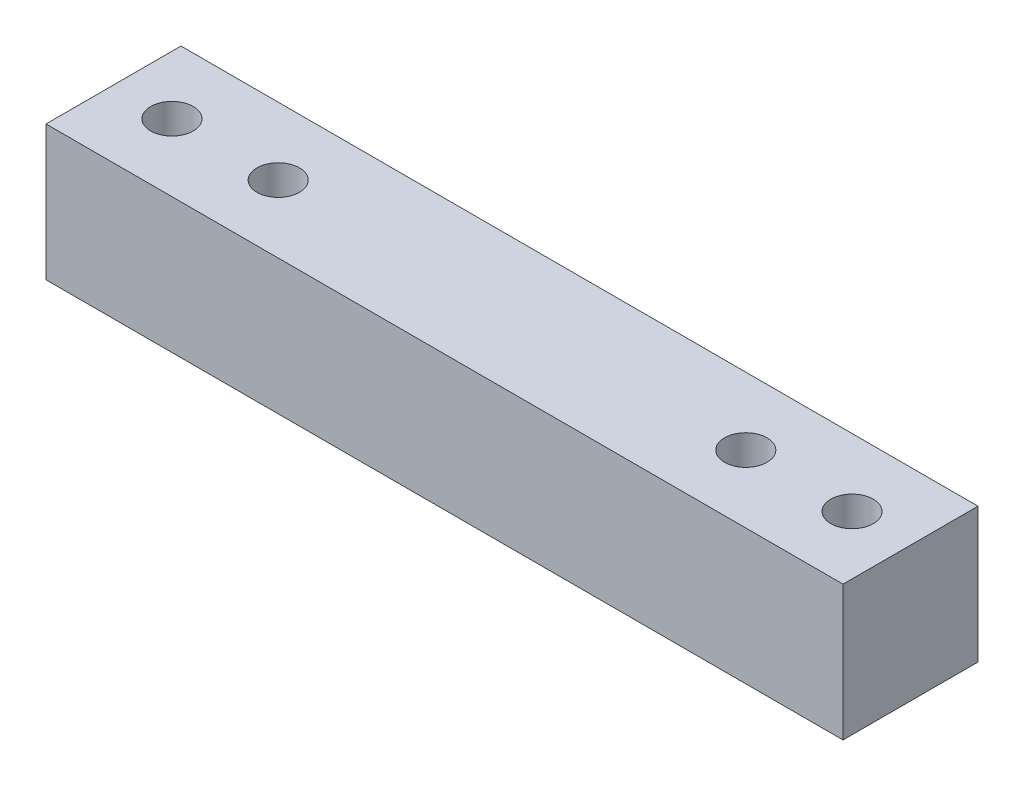
SolidWorks part; units mm, degrees
material "Alloy Steel"
ref_plane "Front Plane" through (0, 0, 0) normal (0, 0, 1) x (1, 0, 0)
ref_plane "Top Plane" through (0, 0, 0) normal (0, 1, 0) x (1, 0, 0)
ref_plane "Right Plane" through (0, 0, 0) normal (1, 0, 0) x (0, 0, -1)
sketch "Sketch1" plane through (0, 0, 0) normal (0, 1, 0) x (1, 0, 0)
  line L1 (0, 0) -> (75, 0)
  line L2 (0, 0) -> (0, 12.7)
  line L3 (0, 12.7) -> (75, 12.7)
  line L4 (75, 0) -> (75, 12.7)
  dimension "D1" = 75
  dimension "D2" = 12.7
extrude "Boss-Extrude1" add sketch "Sketch1" along normal blind 12.7
sketch "Sketch2" plane through (0, 12.7, 0) normal (0, 1, 0) x (1, 0, 0)
  line L1 (0, 0) -> (75, 0) construction
  line L6 (0, 12.7) -> (0, 0) construction
  circle A0 centre (5.5, 6.35) radius 2
  circle A1 centre (15.5, 6.35) radius 2
  circle A2 centre (59.5, 6.35) radius 2
  circle A3 centre (69.5, 6.35) radius 2
  dimension "D1" = 4
  dimension "D5" = 5.5
  dimension "D2" = 44
  dimension "D3" = 10
  dimension "D4" = 6.35
  dimension "D6" = 10
extrude "Cut-Extrude1" cut sketch "Sketch2" against normal through all
sketch "Sketch3" plane through (0, 0, 0) normal (-1, 0, 0) x (0, 0, 1)
  line L0 (-12.7, 12.7) -> (-12.7, 0) construction
  line L1 (-12.7, 0) -> (0, 0) construction
  text T0 "5kg"
  dimension "D1" = 1.6
  dimension "D2" = 4.5
extrude "Boss-Extrude2" add sketch "Sketch3" along normal blind 1
